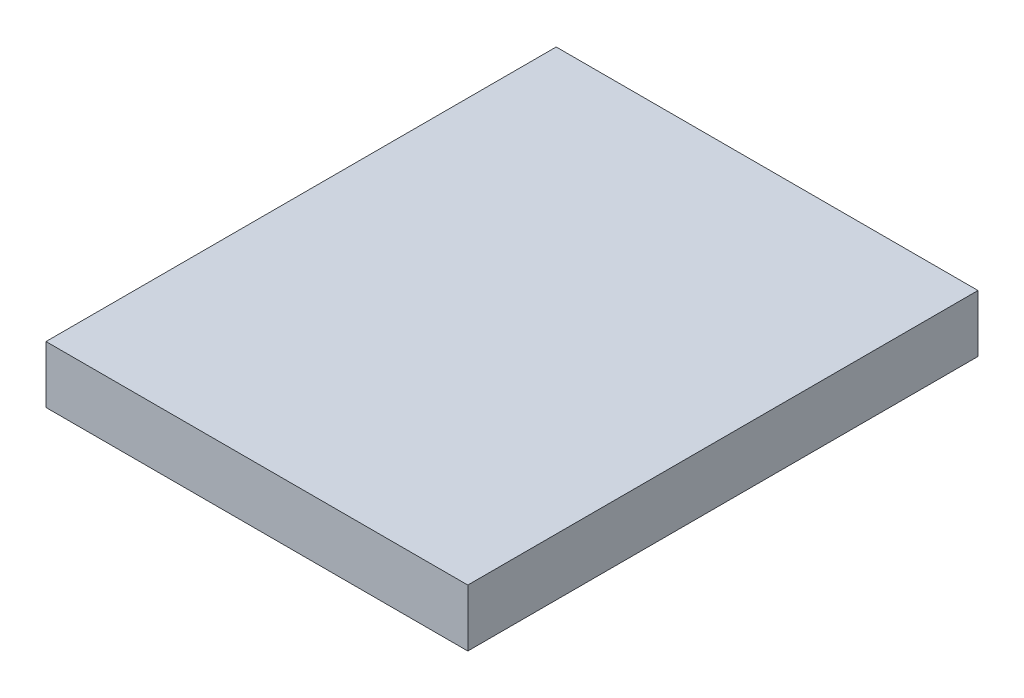
SolidWorks part; units mm, degrees
ref_plane "Front Plane" through (0, 0, 0) normal (0, 0, 1) x (1, 0, 0)
ref_plane "Top Plane" through (0, 0, 0) normal (0, 1, 0) x (1, 0, 0)
ref_plane "Right Plane" through (0, 0, 0) normal (1, 0, 0) x (0, 0, -1)
sketch "Sketch1" plane through (0, 0, 0) normal (0, 0, 1) x (1, 0, 0)
  line L0 (0, 150) -> (0, 0)
  line L1 (0, 150) -> (1106.9725, 150)
  line L3 (0, 0) -> (1106.9725, 0)
  line L4 (1106.9725, 150) -> (1106.9725, 0)
extrude "Boss-Extrude1" add sketch "Sketch1" along normal mid plane 1339 contours L1 L4 L3 L0
